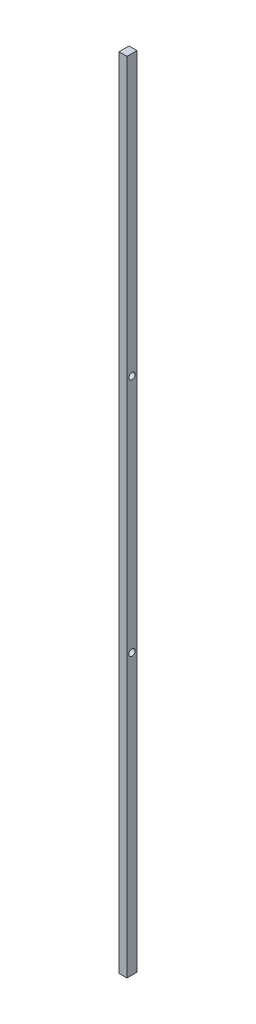
SolidWorks part; units mm, degrees
ref_plane "前视基准面" through (0, 0, 0) normal (0, 0, 1) x (1, 0, 0)
ref_plane "上视基准面" through (0, 0, 0) normal (0, 1, 0) x (1, 0, 0)
ref_plane "右视基准面" through (0, 0, 0) normal (1, 0, 0) x (0, 0, -1)
other "Configuration Table"
sketch "草图1" plane through (0, 0, 0) normal (0, 1, 0) x (1, 0, 0)
  line L1 (0, 0) -> (4, 0)
  line L2 (0, 0) -> (0, 5)
  line L3 (0, 5) -> (4, 5)
  line L4 (4, 0) -> (4, 5)
  line L5 (0, 0) -> (4, 5) construction
  line L6 (0, 5) -> (4, 0) construction
  point P4 (2, 2.5)
  dimension "D1" = 4
  dimension "D2" = 5
extrude "凸台-拉伸1" add sketch "草图1" along normal blind 400
sketch "草图2" plane through (4, 0, 0) normal (1, 0, 0) x (0, 0, -1)
  line L0 (5, 200) -> (5, 260)
  line L1 (5, 400) -> (5, 0) construction
  line L2 (5, 200) -> (5, 140)
  line L3 (5, 140) -> (2.5, 140)
  line L4 (5, 260) -> (2.5, 260)
  circle A0 centre (2.5, 140) radius 1.6
  circle A1 centre (2.5, 260) radius 1.6
  dimension "D4" = 3.2
  dimension "D6" = 3.2
  dimension "D1" = 60
  dimension "D2" = 60
  dimension "D3" = 2.5
  dimension "D5" = 2.5
extrude "切除-拉伸1" cut sketch "草图2" against normal blind 400
